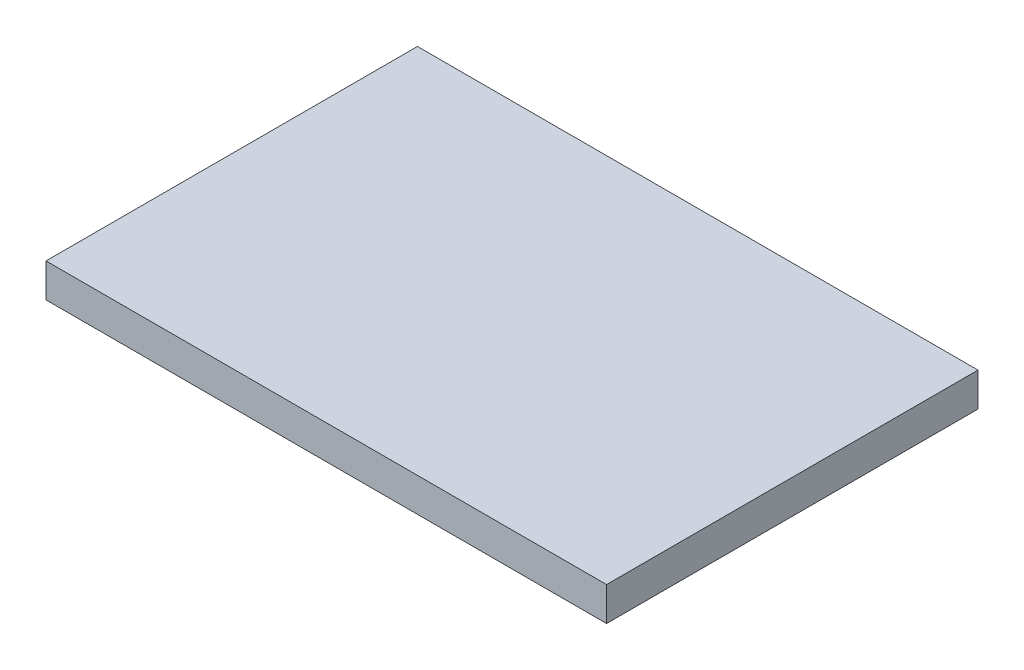
SolidWorks part; units mm, degrees
ref_plane "Front Plane" through (0, 0, 0) normal (0, 0, 1) x (1, 0, 0)
ref_plane "Top Plane" through (0, 0, 0) normal (0, 1, 0) x (1, 0, 0)
ref_plane "Right Plane" through (0, 0, 0) normal (1, 0, 0) x (0, 0, -1)
sketch "Sketch1" plane through (0, 0, 0) normal (0, 1, 0) x (1, 0, 0)
  line L1 (-41.5, -27.5) -> (41.5, -27.5)
  line L2 (-41.5, -27.5) -> (-41.5, 27.5)
  line L3 (-41.5, 27.5) -> (41.5, 27.5)
  line L4 (41.5, -27.5) -> (41.5, 27.5)
  line L5 (-41.5, -27.5) -> (41.5, 27.5) construction
  line L6 (-41.5, 27.5) -> (41.5, -27.5) construction
  point P0 (0, 0)
  dimension "D1" = 55
  dimension "D2" = 83
extrude "Boss-Extrude1" add sketch "Sketch1" along normal blind 5
